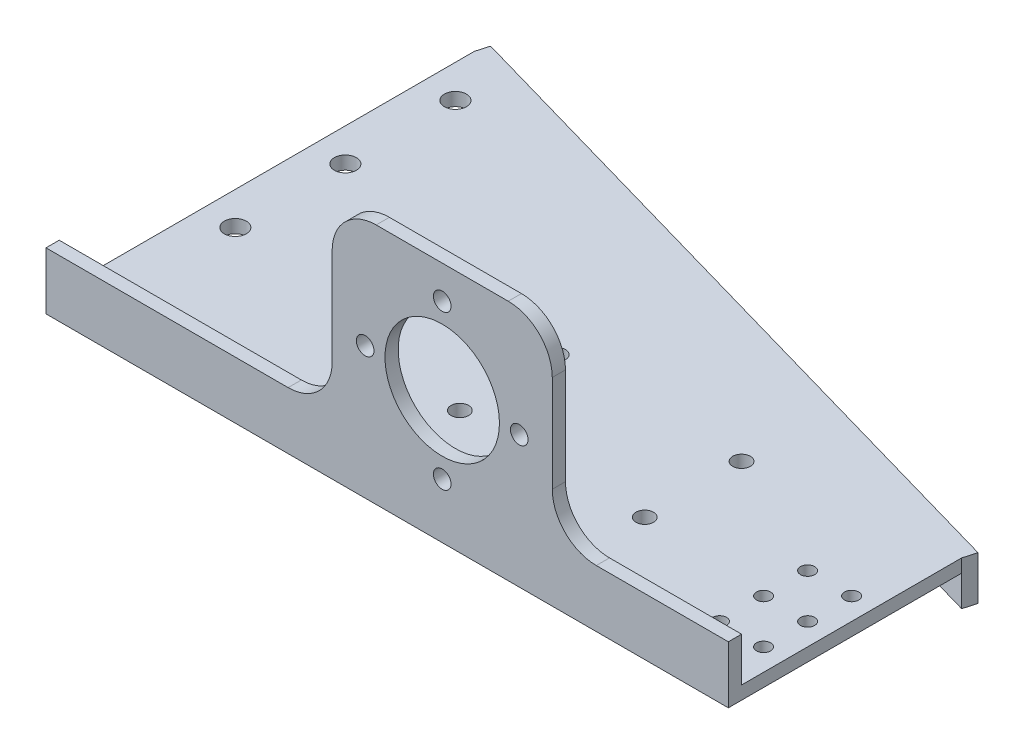
SolidWorks part; units mm, degrees
ref_plane "前视基准面" through (0, 0, 0) normal (0, 0, 1) x (1, 0, 0)
ref_plane "上视基准面" through (0, 0, 0) normal (0, 1, 0) x (1, 0, 0)
ref_plane "右视基准面" through (0, 0, 0) normal (1, 0, 0) x (0, 0, -1)
sketch "草图1" plane through (0, 0, 0) normal (0, 1, 0) x (1, 0, 0)
  line L0 (70, -45) -> (70, 5)
  line L1 (-85, 45) -> (70, 45)
  line L2 (-85, 45) -> (-85, -45)
  line L3 (-85, -45) -> (70, -45)
  line L4 (70, 45) -> (70, -45)
  line L5 (-85, 45) -> (70, -45) construction
  line L6 (-85, -45) -> (70, 45) construction
  line L7 (-70, 45) -> (70, 5)
  line L8 (-85, 45) -> (-70, 45)
  line L9 (-70, 45) -> (-85, 49.2857)
  line L10 (-85, 49.2857) -> (-85, 45)
  point P0 (0, 0)
extrude "凸台-拉伸1" add sketch "草图1" along normal blind 3 contours L7 L1 L2 L3 L0 | L9 L10 L1
hole_wizard "Ø5.0 (5) 直径孔2" positions "草图3" profile "草图2" hole size "Ø5.0" standard "GB" end condition through all
sketch "草图3" plane through (0, 3, 0) normal (0, 1, 0) x (1, 0, 0)
  line L0 (-85, -37.5) -> (-77.5, -37.5)
  line L1 (-85, 49.2857) -> (-85, -45) construction
  line L2 (-77.5, -37.5) -> (-77.5, -45)
  line L3 (-85, -45) -> (70, -45) construction
  line L4 (-77.5, -37.5) -> (-77.5, -12.5)
  line L7 (-77.5, 37.5) -> (-85, 37.5)
  line L9 (-77.5, 37.5) -> (-77.5, 12.5)
  point P2 (-77.5, -37.5)
  point P14 (-77.5, -12.5)
  point P20 (-77.5, 37.5)
  point P27 (-77.5, 12.5)
sketch "草图2" plane through (-77.5, 3, 37.5) normal (1, 0, 0) x (0, 0, 1)
  line L0 (0, 0) -> (0, 3)
  line L1 (0, 3) -> (2.5, 3)
  line L2 (2.5, 3) -> (2.5, 0)
  line L5 (2.5, 0) -> (0, 0)
  line L11 (0, -6.35) -> (0, 107.95) construction
  dimension "通孔孔直径" = 5
  dimension "通孔孔深度" = 3
hole_wizard "Ø3.2 (3.2) 直径孔2" positions "草图7" profile "草图6" hole size "Ø3.2" standard "GB" end condition through all
sketch "草图7" plane through (0, 0, 0) normal (0, -1, 0) x (-1, 0, 0)
  line L0 (-70, -35) -> (-65, -35)
  line L1 (-70, -45) -> (-70, 5) construction
  line L2 (-65, -35) -> (-65, -45)
  line L3 (85, -45) -> (-70, -45) construction
  point P2 (-65, -35)
sketch "草图6" plane through (65, 0, 35) normal (1, 0, 0) x (0, 0, -1)
  line L0 (0, 0) -> (0, 3)
  line L1 (0, 3) -> (1.6, 3)
  line L2 (1.6, 3) -> (1.6, 0)
  line L5 (1.6, 0) -> (0, 0)
  line L11 (0, -6.35) -> (0, 107.95) construction
  dimension "通孔孔直径" = 3.2
  dimension "通孔孔深度" = 3
pattern_linear "阵列(线性)1" count 3 spacing 10 along (0, 0, -1) count 2 spacing 10 along (-1, 0, 0) of "Ø3.2 (3.2) 直径孔2"
sketch "草图8" plane through (0, 3, 0) normal (0, 1, 0) x (1, 0, 0)
  line L0 (-85, 49.2857) -> (70, 5)
  line L1 (70, 5) -> (70.8242, 7.8846)
  line L2 (70.8242, 7.8846) -> (-84.1758, 52.1703)
  line L3 (-84.1758, 52.1703) -> (-85, 49.2857)
extrude "凸台-拉伸2" add sketch "草图8" against normal blind 10
sketch "草图9" plane through (0, 0, 0) normal (0, -1, 0) x (-1, 0, 0)
  line L0 (85, -45) -> (-70, -45)
  line L1 (-70, -45) -> (-70, -48)
  line L2 (-70, -48) -> (85, -48)
  line L3 (85, -48) -> (85, -45)
extrude "凸台-拉伸3" add sketch "草图9" against normal blind 13
sketch "草图10" plane through (0, 0, 0) normal (0, -1, 0) x (1, 0, 0)
  line L0 (70, 48) -> (30, 48) construction
  line L1 (70, 48) -> (-85, 48) construction
  line L2 (30, 48) -> (-20, 48)
  line L3 (-20, 48) -> (-20, 45)
  line L4 (-20, 45) -> (30, 45)
  line L5 (30, 45) -> (30, 48)
extrude "凸台-拉伸4" add sketch "草图10" against normal blind 55
sketch "草图12" plane through (0, 0, 48) normal (0, 0, 1) x (1, 0, 0)
  line L0 (5, 55) -> (5, 30) construction
  line L1 (30, 55) -> (-20, 55) construction
  circle A0 centre (5, 30) radius 13
extrude "切除-拉伸1" cut sketch "草图12" against normal blind 3
sketch "草图13" plane through (0, 0, 48) normal (0, 0, 1) x (1, 0, 0)
  line L0 (5, 30) -> (5, 47.5)
  circle A0 centre (5, 47.5) radius 2
extrude "切除-拉伸2" cut sketch "草图13" against normal blind 3
pattern_circular "阵列(圆周)1" count 4 over 360 about axis through (5, 30, 0) along (0, 0, 1) of "切除-拉伸2"
fillet "圆角1" radius 10 4 edges at (-20, 13, 46.5) (30, 13, 46.5) (-20, 55, 46.5) (30, 55, 46.5)
hole_wizard "Ø4.0 (4) 直径孔2" positions "草图15" profile "草图14" hole size "Ø4.0" standard "GB" end condition through all
sketch "草图15" plane through (0, 3, 0) normal (0, 1, 0) x (1, 0, 0)
  line L0 (-85, -45) -> (-85, -1)
  line L1 (-85, 49.2857) -> (-85, -45) construction
  line L8 (-85, -1) -> (5, -1)
  line L9 (5, -1) -> (5, 16.1718)
  line L10 (5, 16.1718) -> (-16, 16.1718)
  line L11 (-16, 16.1718) -> (26, 16.1718)
  line L13 (5, -1) -> (5, -23)
  point P33 (-16, -1)
  point P35 (-16, -23)
  point P37 (26, -23)
  point P39 (26, -1)
sketch "草图14" plane through (-16, 3, 1) normal (1, 0, 0) x (0, 0, 1)
  line L0 (0, 0) -> (0, 10)
  line L1 (0, 10) -> (2, 10)
  line L2 (2, 10) -> (2, 0)
  line L5 (2, 0) -> (0, 0)
  line L11 (0, -6.35) -> (0, 107.95) construction
  dimension "通孔孔直径" = 4
  dimension "通孔孔深度" = 10
